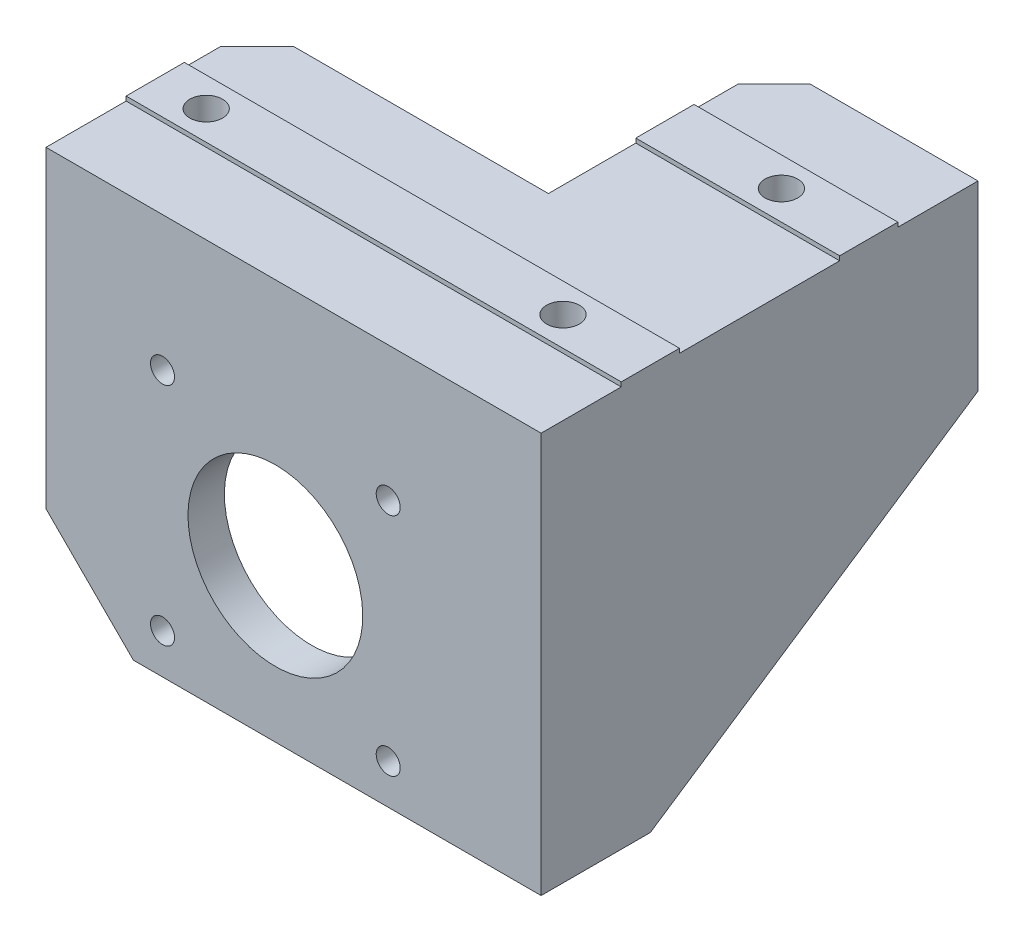
SolidWorks part; units mm, degrees
material "3D printed plastic"
ref_plane "Front Plane" through (0, 0, 0) normal (0, 0, 1) x (1, 0, 0)
ref_plane "Top Plane" through (0, 0, 0) normal (0, 1, 0) x (1, 0, 0)
ref_plane "Right Plane" through (0, 0, 0) normal (1, 0, 0) x (0, 0, -1)
sketch "Sketch1" plane through (0, 0, 0) normal (1, 0, 0) x (0, 0, -1)
  line L1 (-55, 0) -> (0, 0)
  line L2 (-55, 0) -> (-55, -43)
  line L5 (-55, -43) -> (-60, -43)
  line L6 (0, 0) -> (0, 12)
  line L7 (0, 12) -> (-60, 12)
  line L8 (-60, -43) -> (-60, 12)
  dimension "D1" = 12
  dimension "D2" = 5
  dimension "D3" = 60
  dimension "D4" = 43
extrude "Boss-Extrude1" add sketch "Sketch1" along normal mid plane 63
sketch "Sketch2" plane through (0, 0, 55) normal (0, 0, -1) x (-1, 0, 0)
  line L0 (-15.5, -6.5) -> (15.5, -37.5) construction
  line L1 (-15.5, -6.5) -> (15.5, -6.5) construction
  line L2 (-15.5, -6.5) -> (-15.5, -37.5) construction
  line L3 (-15.5, -37.5) -> (15.5, -37.5) construction
  line L4 (15.5, -6.5) -> (15.5, -37.5) construction
  line L5 (0, 0) -> (0, -22) construction
  line L6 (-31.5, 0) -> (31.5, 0) construction
  circle A0 centre (0, -22) radius 12
  circle A1 centre (-15.5, -6.5) radius 1.65
  circle A2 centre (-15.5, -37.5) radius 1.65
  circle A3 centre (15.5, -37.5) radius 1.65
  circle A4 centre (15.5, -6.5) radius 1.65
  dimension "D1" = 24
  dimension "D3" = 3.3
  dimension "D2" = 31
  dimension "D4" = 22
extrude "Cut-Extrude1" cut sketch "Sketch2" against normal through all
sketch "Sketch3" plane through (0, 0, 0) normal (0, -1, 0) x (1, 0, 0)
  line L1 (-31.5, 0) -> (8.5, 0)
  line L2 (-31.5, 0) -> (-31.5, 31)
  line L3 (-31.5, 31) -> (8.5, 31)
  line L4 (8.5, 0) -> (8.5, 31)
  dimension "D1" = 31
  dimension "D2" = 40
extrude "Cut-Extrude2" cut sketch "Sketch3" against normal through all
sketch "Sketch7" plane through (31.5, 0, 0) normal (1, 0, 0) x (0, 0, -1)
  line L0 (-60, -43) -> (-45, -43)
  line L1 (-45, -43) -> (0, -13)
  line L2 (0, -13) -> (0, 12)
  line L3 (0, 12) -> (-60, 12)
  line L4 (-60, 12) -> (-60, -43)
  dimension "D1" = 25
  dimension "D2" = 15
extrude "Boss-Extrude2" add sketch "Sketch7" along normal blind 5
sketch "Sketch8" plane through (0, 12, 0) normal (0, 1, 0) x (1, 0, 0)
  line L0 (-31.5, -31) -> (-31.5, -60) construction
  line L1 (-31.5, -41) -> (36.5, -41)
  line L2 (-31.5, -41) -> (-31.5, -49)
  line L3 (-31.5, -49) -> (36.5, -49)
  line L4 (36.5, -41) -> (36.5, -49)
  line L6 (8.5, 0) -> (8.5, -31) construction
  line L7 (36.5, -11) -> (8.5, -11)
  line L8 (36.5, -11) -> (36.5, -19)
  line L9 (36.5, -19) -> (8.5, -19)
  line L10 (8.5, -11) -> (8.5, -19)
  line L11 (8.5, -15) -> (36.5, -15) construction
  line L12 (36.5, -45) -> (-31.5, -45) construction
  line L13 (36.5, -60) -> (-31.5, -60) construction
  line L14 (36.5, 0) -> (36.5, -60) construction
  dimension "D1" = 30
  dimension "D2" = 8
  dimension "D3" = 15
extrude "Boss-Extrude3" add sketch "Sketch8" along normal blind 0.6
hole_wizard "CBORE for M4 Hex Socket Head Cap Screw1" positions "Sketch5" profile "Sketch4" counterbore size "M4" standard "DIN" end condition through all
sketch "Sketch5" plane through (0, 0, 0) normal (0, -1, 0) x (-1, 0, 0)
  line L0 (24.5, -60) -> (24.5, -45) construction
  line L1 (-36.5, -60) -> (31.5, -60) construction
  line L2 (24.5, -45) -> (-24.5, -45) construction
  line L3 (-24.5, -45) -> (-24.5, -15) construction
  line L5 (31.5, -55) -> (31.5, -31) construction
  line L7 (-31.5, -45) -> (-31.5, 0) construction
  point P0 (24.5, -45)
  point P2 (-24.5, -45)
  point P4 (-24.5, -15)
  dimension "D1" = 30
  dimension "D2" = 15
  dimension "D3" = 7
  dimension "D4" = 7
sketch "Sketch4" plane through (-24.5, 0, 45) normal (1, 0, 0) x (0, 0, -1)
  line L0 (0, 0) -> (0, 12.6)
  line L1 (0, 12.6) -> (2.25, 12.6)
  line L3 (2.25, 12.6) -> (2.25, 8)
  line L4 (2.25, 8) -> (5, 8)
  line L5 (5, 8) -> (5, 0)
  line L7 (5, 0) -> (0, 0)
  line L11 (0, -6.35) -> (0, 107.95) construction
  dimension "Thru Hole Dia." = 4.5
  dimension "Thru Hole Depth" = 12.6
  dimension "C'Bore Dia." = 10
  dimension "C'Bore Depth" = 8
chamfer "Chamfer1" distance 12 angle 45 1 edges at (-31.5, -43, 57.5)
chamfer "Chamfer2" distance 5 angle 45 2 edges at (-31.5, 6, 31) (8.5, 6, 0)
